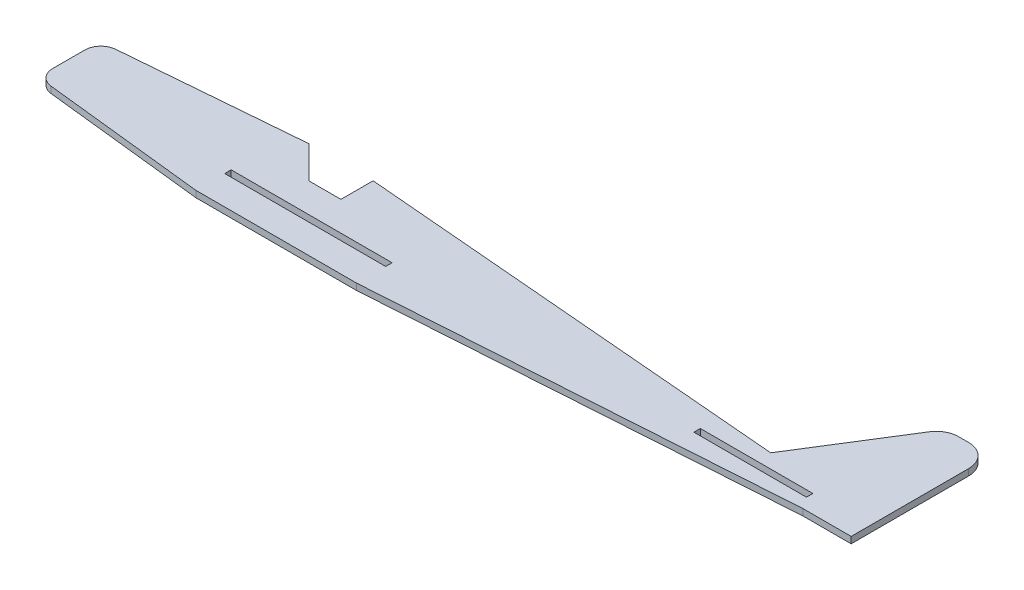
SolidWorks part; units mm, degrees
ref_plane "Front Plane" through (0, 0, 0) normal (0, 0, 1) x (1, 0, 0)
ref_plane "Top Plane" through (0, 0, 0) normal (0, 1, 0) x (1, 0, 0)
ref_plane "Right Plane" through (0, 0, 0) normal (1, 0, 0) x (0, 0, -1)
sketch "Sketch1" plane through (0, 0, 0) normal (0, 1, 0) x (1, 0, 0)
  line L0 (-120.4055, 10.8404) -> (-64.9903, 15.4583)
  line L2 (-124.9903, 5.8576) -> (-124.9903, -4.1424)
  line L3 (-69.9903, -14.6517) -> (-19.9903, -14.6517)
  line L4 (125.0097, 15.5628) -> (125.0097, -5.9744)
  line L5 (125.0097, 15.5628) -> (125.0097, 30.5628)
  line L7 (-120.535, -9.1126) -> (-69.9903, -14.6517)
  line L10 (-19.9903, -14.6517) -> (110.0097, -5.9744)
  line L11 (90.0097, 4.0256) -> (-44.9903, 15.4583)
  line L12 (110.0097, -5.9744) -> (125.0097, -5.9744)
  line L13 (-44.9903, 15.4583) -> (-44.9903, 5.4583)
  line L14 (-44.9903, 5.4583) -> (-54.9903, 5.4583)
  line L15 (-54.9903, 5.4583) -> (-64.9903, 15.4583)
  line L16 (118.0097, 37.5628) -> (114.8856, 37.5628)
  line L17 (108.9527, 34.2778) -> (90.0097, 4.0256)
  line L18 (-69.9903, -3.6517) -> (-19.9903, -3.6517)
  line L19 (-69.9903, -3.6517) -> (-69.9903, -5.6517)
  line L20 (-69.9903, -5.6517) -> (-19.9903, -5.6517)
  line L21 (-19.9903, -3.6517) -> (-19.9903, -5.6517)
  arc A0 (-120.4055, 10.8404) -> (-124.9903, 5.8576) centre (-119.9903, 5.8576) ccw
  arc A1 (-120.535, -9.1126) -> (-124.9903, -4.1424) centre (-119.9903, -4.1424) cw
  arc A2 (114.8856, 37.5628) -> (108.9527, 34.2778) centre (114.8856, 30.5628) ccw
  arc A3 (125.0097, 30.5628) -> (118.0097, 37.5628) centre (118.0097, 30.5628) ccw
  point P0 (0, 0)
  point P16 (111.0097, 37.5628)
  point P27 (125.0097, 37.5628)
  dimension "D3" = 5
  dimension "D1" = 5
  dimension "D12" = 14
  dimension "D13" = 7
  dimension "D7" = 7
  dimension "D2" = 15
  dimension "D4" = 10
  dimension "D5" = 55
  dimension "D6" = 250
  dimension "D8" = 50
  dimension "D9" = 10
  dimension "D10" = 10
  dimension "D11" = 20
  dimension "D14" = 2
  dimension "D15" = 10
  dimension "D16" = 20
  dimension "D17" = 135
  dimension "D18" = 22
  dimension "D19" = 60
  dimension "D20" = 9
extrude "Boss-Extrude1" add sketch "Sketch1" along normal blind 2
sketch "Sketch6" plane through (0, 2, 0) normal (0, 1, 0) x (1, 0, 0)
  line L1 (72.5097, -0.3622) -> (107.5097, -0.3622)
  line L2 (72.5097, -0.3622) -> (72.5097, -2.3622)
  line L3 (72.5097, -2.3622) -> (107.5097, -2.3622)
  line L4 (107.5097, -0.3622) -> (107.5097, -2.3622)
  line L5 (72.5097, -2.3622) -> (107.5097, -0.3622) construction
  line L6 (107.5097, -2.3622) -> (72.5097, -0.3622) construction
  line L7 (90.0097, -1.3622) -> (90.0097, 4.0256) construction
  line L8 (90.0097, 4.0256) -> (90.0097, -7.3094) construction
  line L9 (-19.9903, -14.6517) -> (110.0097, -5.9744) construction
  point P4 (90.0097, -0.3622)
  point P6 (90.0097, -1.3622)
  dimension "D1" = 35
  dimension "D2" = 2
extrude "Cut-Extrude1" cut sketch "Sketch6" against normal blind 2
